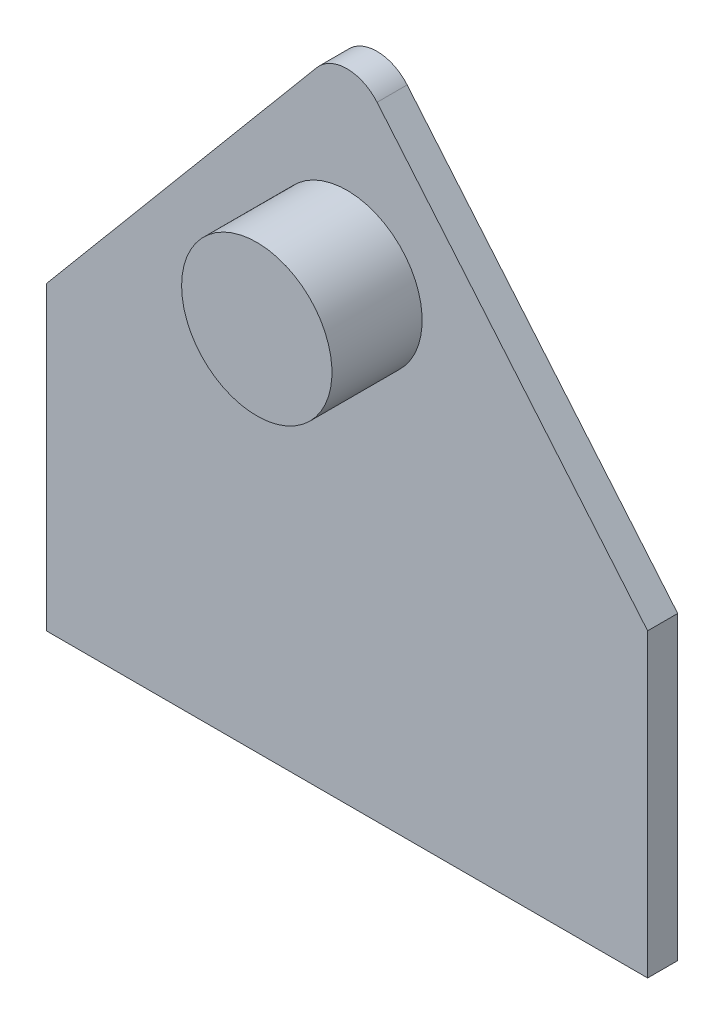
SolidWorks part; units mm, degrees
ref_plane "Front Plane" through (0, 0, 0) normal (0, 0, 1) x (1, 0, 0)
ref_plane "Top Plane" through (0, 0, 0) normal (0, 1, 0) x (1, 0, 0)
ref_plane "Right Plane" through (0, 0, 0) normal (1, 0, 0) x (0, 0, -1)
sketch "Sketch1" plane through (0, 0, 0) normal (0, 0, 1) x (1, 0, 0)
  line L0 (-10.1994, 0) -> (-10.1994, 12.7)
  line L1 (-10.1994, 12.7) -> (1.2293, 26.3203)
  line L2 (3.7718, 26.3203) -> (15.2006, 12.7)
  line L3 (15.2006, 12.7) -> (15.2006, 0)
  line L4 (15.2006, 0) -> (-10.1994, 0)
  arc A0 (1.2293, 26.3203) -> (3.7718, 26.3203) centre (2.5006, 25.2536) cw
  dimension "D8" = 1.6595
  dimension "D1" = 25.4
  dimension "D2" = 12.7
  dimension "D3" = 12.7
  dimension "D4" = 140
  dimension "D5" = 140
  dimension "D6" = 17.78
  dimension "D7" = 17.78
extrude "Boss-Extrude2" add sketch "Sketch1" along normal blind 1.27
sketch "Sketch2" plane through (0, 0, 1.27) normal (0, 0, 1) x (1, 0, 0)
  line L0 (2.5006, 26.9131) -> (2.5006, 19.2931) construction
  arc A0 (3.7718, 26.3203) -> (1.2293, 26.3203) centre (2.5006, 25.2536) ccw construction
  circle A1 centre (2.5006, 19.2931) radius 3.175
  dimension "D1" = 6.35
  dimension "D2" = 7.62
extrude "Boss-Extrude4" add sketch "Sketch2" along normal blind 3.81
